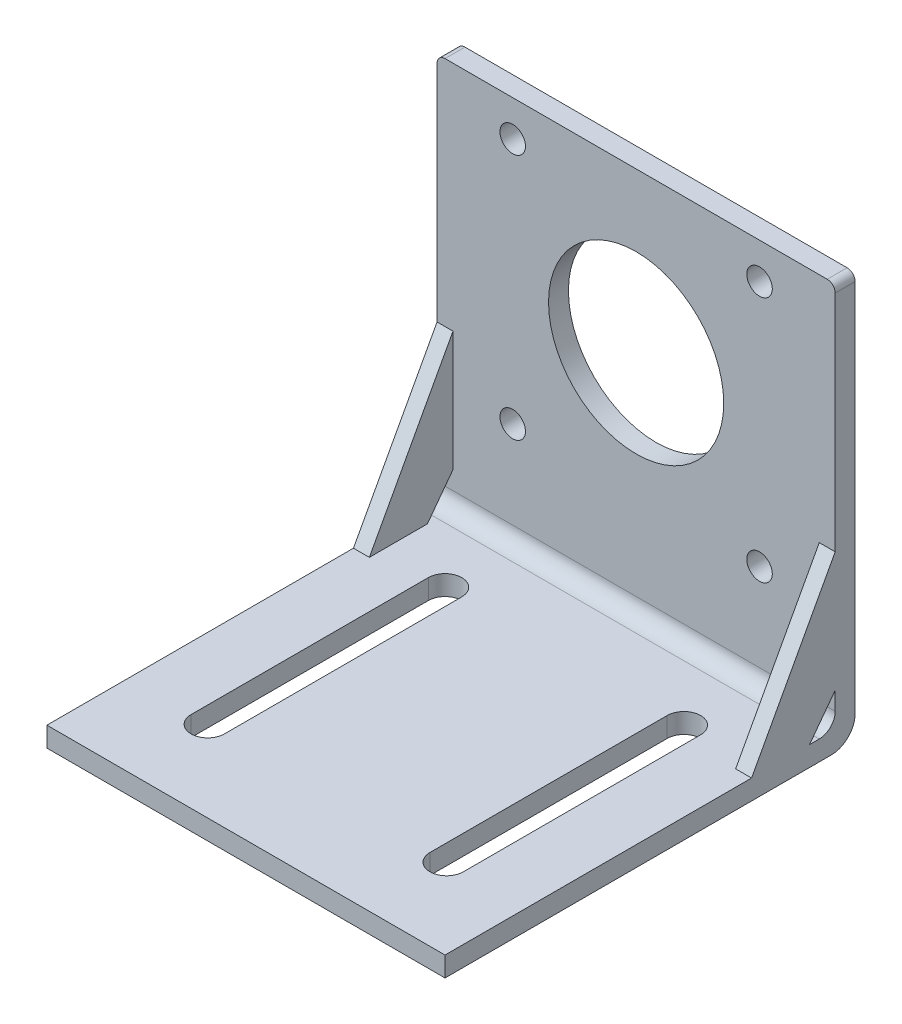
SolidWorks part; units mm, degrees
ref_plane "Plan de face" through (0, 0, 0) normal (0, 0, 1) x (1, 0, 0)
ref_plane "Plan de dessus" through (0, 0, 0) normal (0, 1, 0) x (1, 0, 0)
ref_plane "Plan de droite" through (0, 0, 0) normal (1, 0, 0) x (0, 0, -1)
ref_plane "Plan1" through (0, 0, 0) normal (0, 0, -1) x (-1, 0, 0)
sketch "Esquisse1" plane through (0, 0, 0) normal (0, 0, -1) x (-1, 0, 0)
  line L0 (-11.5004, -0.8498) -> (-11.5004, 49.1502)
  line L1 (-61.5004, -0.8498) -> (-11.5004, -0.8498)
  line L5 (-12.5004, 50.1502) -> (-60.5004, 50.1502)
  line L11 (-61.5004, 49.1502) -> (-61.5004, -0.8498)
  circle A0 centre (-36.5004, 30.1502) radius 11
  circle A1 centre (-52.0004, 14.6502) radius 1.6
  circle A2 centre (-52.0004, 45.6502) radius 1.6
  circle A3 centre (-21.0004, 14.6502) radius 1.6
  circle A4 centre (-21.0004, 45.6502) radius 1.6
  arc A5 (-61.5004, 49.1502) -> (-60.5004, 50.1502) centre (-60.5004, 49.1502) cw
  arc A6 (-12.5004, 50.1502) -> (-11.5004, 49.1502) centre (-12.5004, 49.1502) cw
  dimension "D1" = 22
  dimension "D3" = 30.1502
  dimension "D4" = 15.5
  dimension "D5" = 15.5
  dimension "D6" = 3.2
  dimension "D7" = 15.5
  dimension "D8" = 15.5
  dimension "D9" = 3.2
  dimension "D10" = 3.2
  dimension "D11" = 15.5
  dimension "D12" = 15.5
  dimension "D13" = 3.2
  dimension "D14" = 15.5
  dimension "D15" = 15.5
  dimension "D25" = 1
  dimension "D26" = 1
  dimension "D16" = 50
  dimension "D17" = 25
  dimension "D18" = 36.5004
  dimension "D19" = 20
  dimension "D20" = 0.8498
extrude "Boss.-Extru.1" add sketch "Esquisse1" against normal blind 2.5
sketch "Esquisse2" plane through (0, 0, 2.5) normal (0, 0, 1) x (1, 0, 0)
  line L1 (61.5004, 49.1502) -> (61.5004, -0.8498) construction
  line L2 (11.5004, -0.8498) -> (61.5004, -0.8498)
  line L4 (11.5004, -0.8498) -> (11.5004, 1.6502)
  line L5 (11.5004, 1.6502) -> (61.5004, 1.6502)
  line L6 (61.5004, -0.8498) -> (61.5004, 1.6502)
  dimension "D1" = 2.5
extrude "Boss.-Extru.2" add sketch "Esquisse2" along normal blind 49
sketch "Esquisse5" plane through (0, 1.6502, 0) normal (0, 1, 0) x (1, 0, 0)
  line L0 (36.5004, 0) -> (36.5004, -51.5) construction
  line L1 (12.5004, 0) -> (60.5004, 0) construction
  line L2 (61.5004, -51.5) -> (11.5004, -51.5) construction
  line L3 (21.5004, -11.5) -> (21.5004, -41.3) construction
  line L4 (23.6004, -11.5) -> (23.6004, -41.3)
  line L5 (19.4004, -11.5) -> (19.4004, -41.3)
  line L6 (61.5004, -2.5) -> (11.5004, -2.5) construction
  line L7 (51.5004, -11.5) -> (51.5004, -41.3) construction
  line L8 (49.4004, -11.5) -> (49.4004, -41.3)
  line L9 (53.6004, -11.5) -> (53.6004, -41.3)
  arc A0 (23.6004, -11.5) -> (19.4004, -11.5) centre (21.5004, -11.5) ccw
  arc A1 (19.4004, -41.3) -> (23.6004, -41.3) centre (21.5004, -41.3) ccw
  arc A2 (49.4004, -11.5) -> (53.6004, -11.5) centre (51.5004, -11.5) cw
  arc A3 (53.6004, -41.3) -> (49.4004, -41.3) centre (51.5004, -41.3) cw
  point P8 (21.5004, -26.4)
  point P17 (51.5004, -26.4)
  dimension "D1" = 4.2
  dimension "D2" = 29.8
  dimension "D3" = 9
  dimension "D4" = 15
extrude "Enlèv. mat.-Extru.1" cut sketch "Esquisse5" against normal through all
fillet "Congé1" radius 3 1 edges at (36.5004, -0.8498, 0)
fillet "Congé2" radius 2 1 edges
sketch "Esquisse4" plane through (11.5004, 0, 0) normal (-1, 0, 0) x (0, 0, 1)
  line L0 (1.9867, 6.6371) -> (6.1167, 1.1093)
  line L1 (1.9867, 21.9498) -> (13.2965, 1.1093)
  line L2 (1.9867, 21.9498) -> (1.9867, 6.6371)
  line L3 (6.1167, 1.1093) -> (13.2965, 1.1093)
extrude "Boss.-Extru.3" add sketch "Esquisse4" against normal blind 2
ref_plane "Plan2" through (36.5004, 0, 0) normal (-1, 0, 0) x (0, 0, 1)
mirror "Symétrie1" about plane through (36.5004, 0, 0) normal (-1, 0, 0) of "Boss.-Extru.3"
